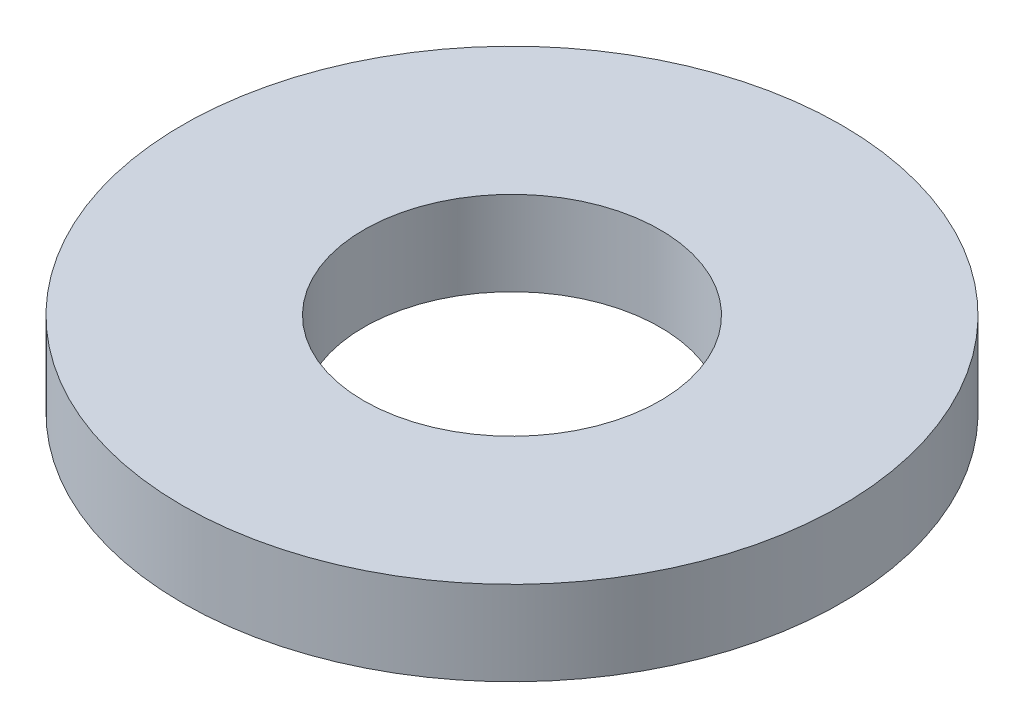
SolidWorks part; units mm, degrees
material "AISI 316 Annealed Stainless Steel Bar (SS)"
ref_plane "Front Plane" through (0, 0, 0) normal (0, 0, 1) x (1, 0, 0)
ref_plane "Top Plane" through (0, 0, 0) normal (0, 1, 0) x (1, 0, 0)
ref_plane "Right Plane" through (0, 0, 0) normal (1, 0, 0) x (0, 0, -1)
ref_plane "Plane1" through (0, 0, 0) normal (0, 0, -1) x (-1, 0, 0)
sketch "Sketch1" plane through (0, 0, 0) normal (0, 0, -1) x (-1, 0, 0)
  line L0 (-7.9375, 2.032) -> (-7.9375, 0)
  line L1 (-7.9375, 0) -> (-3.5687, 0)
  line L2 (-3.5687, 0) -> (-3.5687, 2.032)
  line L3 (-3.5687, 2.032) -> (-7.9375, 2.032)
  line L4 (0, 0) -> (0, 2.032) construction
revolve "Revolve1" add sketch "Sketch1" angle 360 about L4
